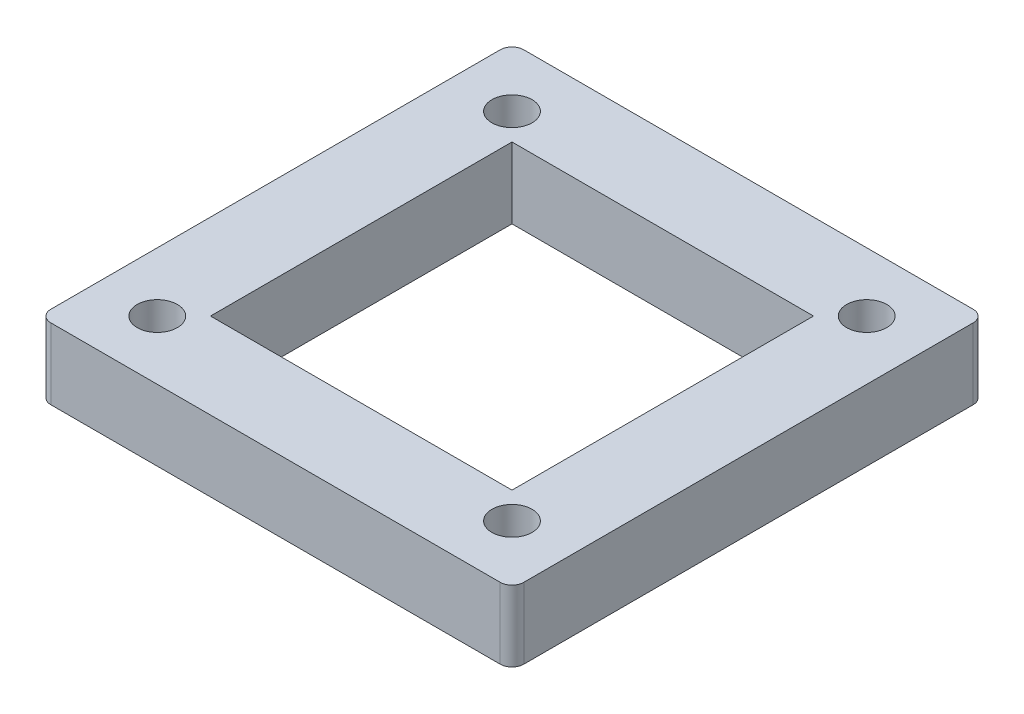
SolidWorks part; units mm, degrees
ref_plane "Front Plane" through (0, 0, 0) normal (0, 0, 1) x (1, 0, 0)
ref_plane "Top Plane" through (0, 0, 0) normal (0, 1, 0) x (1, 0, 0)
ref_plane "Right Plane" through (0, 0, 0) normal (1, 0, 0) x (0, 0, -1)
sketch "Sketch1" plane through (0, 0, 0) normal (0, 1, 0) x (1, 0, 0)
  line L1 (-20, -20) -> (20, -20)
  line L2 (-20, -20) -> (-20, 20)
  line L3 (-20, 20) -> (20, 20)
  line L4 (20, -20) -> (20, 20)
  line L5 (-20, -20) -> (20, 20) construction
  line L6 (-20, 20) -> (20, -20) construction
  line L7 (-12.75, -12.75) -> (12.75, -12.75)
  line L8 (-12.75, -12.75) -> (-12.75, 12.75)
  line L9 (-12.75, 12.75) -> (12.75, 12.75)
  line L10 (12.75, -12.75) -> (12.75, 12.75)
  line L11 (-12.75, -12.75) -> (12.75, 12.75) construction
  line L12 (-12.75, 12.75) -> (12.75, -12.75) construction
  point P0 (0, 0)
  point P6 (0, 0)
  dimension "D1" = 25.5
  dimension "D2" = 40
extrude "Boss-Extrude1" add sketch "Sketch1" along normal blind 6
sketch "Sketch5" plane through (0, 6, 0) normal (0, -1, 0) x (1, 0, 0)
  line L2 (-15, -15) -> (15, -15) construction
  line L3 (-15, -15) -> (-15, 15) construction
  line L4 (-15, 15) -> (15, 15) construction
  line L5 (15, -15) -> (15, 15) construction
  line L6 (-15, -15) -> (15, 15) construction
  line L7 (-15, 15) -> (15, -15) construction
  circle A0 centre (-15, 15) radius 1.7
  circle A1 centre (-15, -15) radius 1.7
  circle A2 centre (15, -15) radius 1.7
  circle A3 centre (15, 15) radius 1.7
  point P0 (0, 0)
  dimension "D1" = 30
  dimension "D2" = 3.4
extrude "Cut-Extrude1" cut sketch "Sketch5" along normal through all
fillet "Fillet1" radius 1 4 edges at (-20, 3, -20) (20, 3, -20) (20, 3, 20) (-20, 3, 20)
